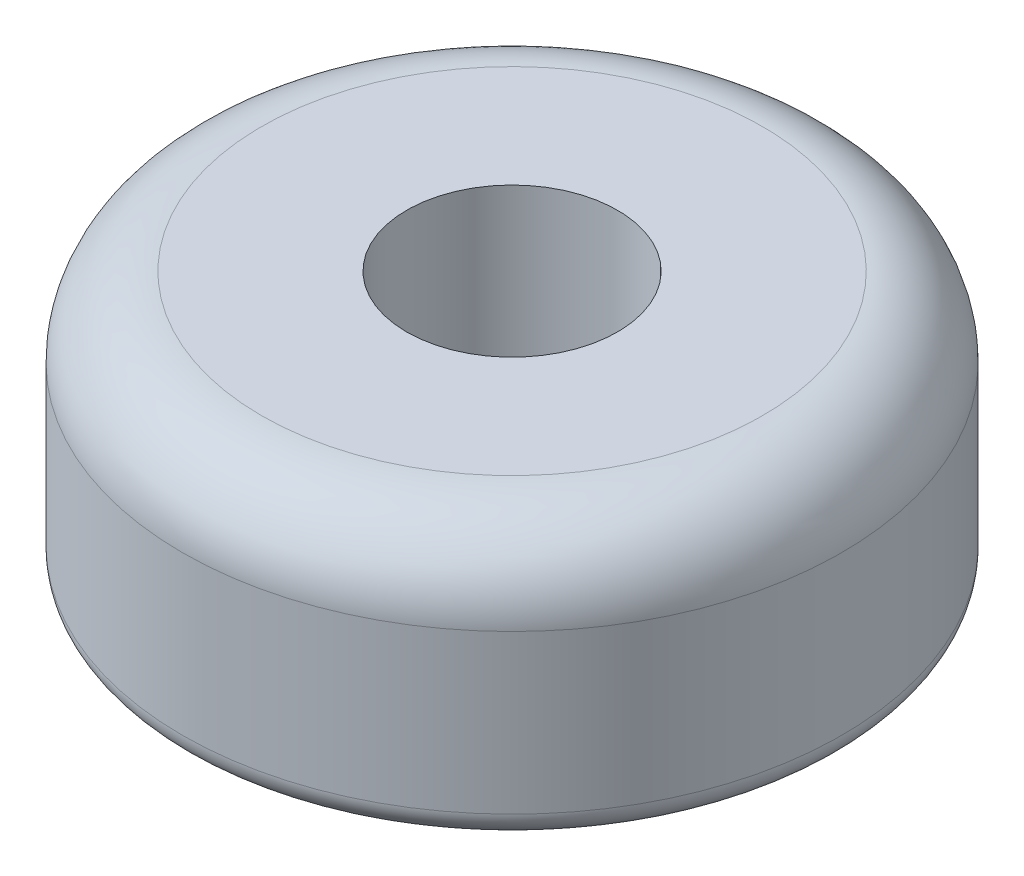
SolidWorks part; units mm, degrees
ref_plane "Front Plane" through (0, 0, 0) normal (0, 0, 1) x (1, 0, 0)
ref_plane "Top Plane" through (0, 0, 0) normal (0, 1, 0) x (1, 0, 0)
ref_plane "Right Plane" through (0, 0, 0) normal (1, 0, 0) x (0, 0, -1)
sketch "Sketch1" plane through (0, 0, 0) normal (0, 1, 0) x (1, 0, 0)
  circle A0 centre (0, 0) radius 12.5
  dimension "D1" = 25
extrude "Boss-Extrude1" add sketch "Sketch1" along normal blind 10
fillet "Fillet1" radius 3 1 edges at (0, 10, 12.5)
sketch "Sketch2" plane through (0, 10, 0) normal (0, 1, 0) x (1, 0, 0)
  circle A0 centre (0, 0) radius 4
  dimension "D1" = 8
extrude "Cut-Extrude1" cut sketch "Sketch2" against normal through all
fillet "Fillet2" radius 1 1 edges at (0, 0, 12.5)
